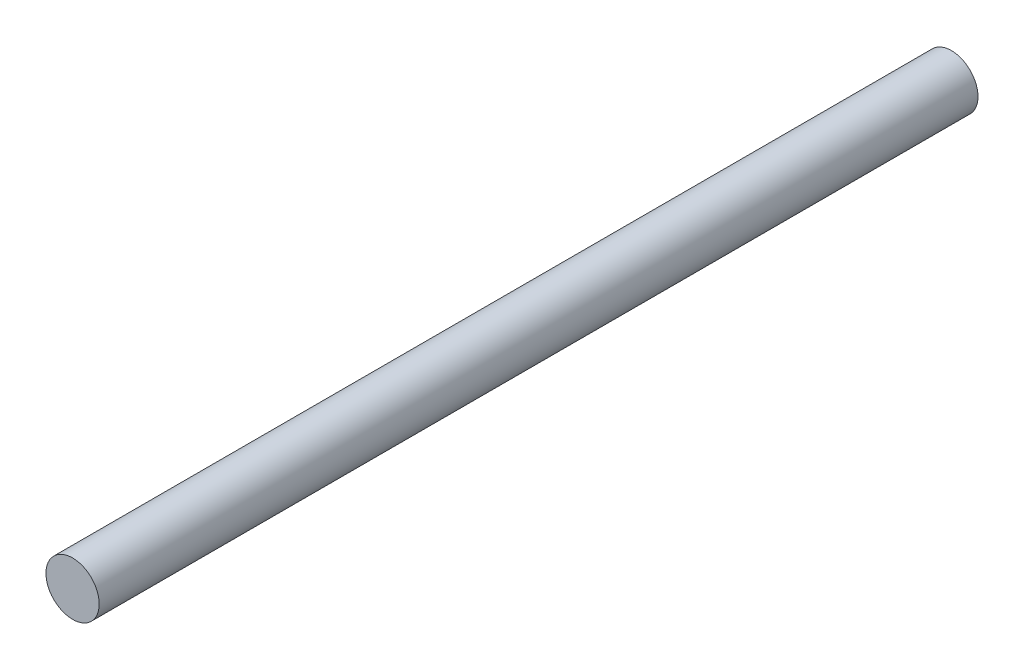
SolidWorks part; units mm, degrees
material "Plain Carbon Steel"
ref_plane "Front Plane" through (0, 0, 0) normal (0, 0, 1) x (1, 0, 0)
ref_plane "Top Plane" through (0, 0, 0) normal (0, 1, 0) x (1, 0, 0)
ref_plane "Right Plane" through (0, 0, 0) normal (1, 0, 0) x (0, 0, -1)
sketch "Sketch1" plane through (0, 0, 0) normal (0, 0, 1) x (1, 0, 0)
  circle A0 centre (0, 0) radius 2
extrude "Boss-Extrude1" add sketch "Sketch1" along normal blind 66
cosmetic thread "Cosmetic Thread1"
cosmetic thread "Cosmetic Thread2"
